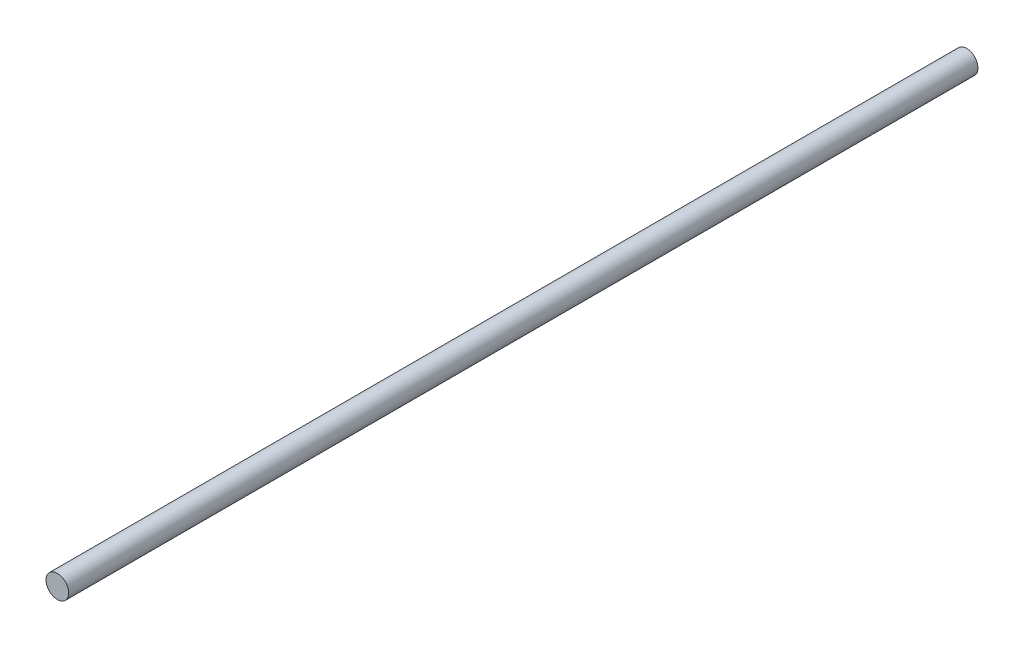
SolidWorks part; units mm, degrees
material "AISI 1020"
ref_plane "前视基准面" through (0, 0, 0) normal (0, 0, 1) x (1, 0, 0)
ref_plane "上视基准面" through (0, 0, 0) normal (0, 1, 0) x (1, 0, 0)
ref_plane "右视基准面" through (0, 0, 0) normal (1, 0, 0) x (0, 0, -1)
sketch "草图1" plane through (0, 0, 0) normal (0, 0, 1) x (1, 0, 0)
  circle A0 centre (0, 0) radius 2.5
  dimension "D1" = 5
extrude "凸台-拉伸1" add sketch "草图1" along normal blind 200
